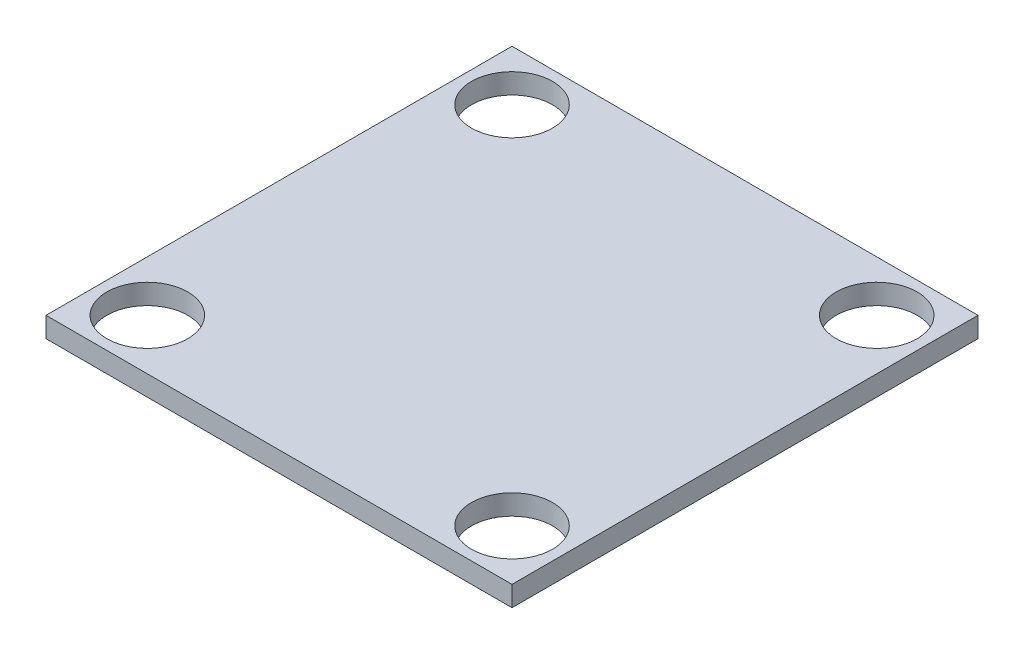
SolidWorks part; units mm, degrees
ref_plane "前基準面" through (0, 0, 0) normal (0, 0, 1) x (1, 0, 0)
ref_plane "上基準面" through (0, 0, 0) normal (0, 1, 0) x (1, 0, 0)
ref_plane "右基準面" through (0, 0, 0) normal (1, 0, 0) x (0, 0, -1)
sketch "草圖1" plane through (0, 0, 0) normal (0, 1, 0) x (1, 0, 0)
  line L1 (-11.5, -11.5) -> (11.5, -11.5)
  line L2 (-11.5, -11.5) -> (-11.5, 11.5)
  line L3 (-11.5, 11.5) -> (11.5, 11.5)
  line L4 (11.5, -11.5) -> (11.5, 11.5)
  line L5 (-11.5, -11.5) -> (11.5, 11.5) construction
  line L6 (-11.5, 11.5) -> (11.5, -11.5) construction
  point P0 (0, 0)
  dimension "D1" = 23
extrude "填料-伸長1" add sketch "草圖1" along normal mid plane 1
hole_wizard "Ø4.0 (4) 直徑孔1" positions "草圖5" profile "草圖6" hole size "Ø4.0" standard "ISO" end condition through all
sketch "草圖5" plane through (0, 0.5, 0) normal (0, 1, 0) x (1, 0, 0)
  line L1 (-9, -9) -> (9, -9)
  line L2 (-9, -9) -> (-9, 9)
  line L3 (-9, 9) -> (9, 9)
  line L4 (9, -9) -> (9, 9)
  line L5 (-9, -9) -> (9, 9) construction
  line L6 (-9, 9) -> (9, -9) construction
  point P2 (9, 9)
  point P81 (-9, -9)
  point P82 (-9, 9)
  point P83 (9, -9)
  point P113 (0, 0)
  point P114 (0, 0)
  point P115 (0, 0)
  point P116 (0, 0)
  point P117 (0, 0)
  point P118 (0, 0)
  point P121 (0, 0)
  point P122 (0, 0)
  point P123 (0, 0)
  point P124 (0, 0)
  point P125 (0, 0)
  point P126 (0, 0)
  point P127 (0, 0)
  point P128 (0, 0)
  dimension "D1" = 18
sketch "草圖6" plane through (9, 0.5, -9) normal (1, 0, 0) x (0, 0, 1)
  line L0 (0, 0) -> (0, 1)
  line L1 (0, 1) -> (2, 1)
  line L2 (2, 1) -> (2, 0)
  line L5 (2, 0) -> (0, 0)
  line L11 (0, -6.35) -> (0, 107.95) construction
  dimension "砮 ふ 畖" = 4
  dimension "砮 ふ瞏 " = 1
